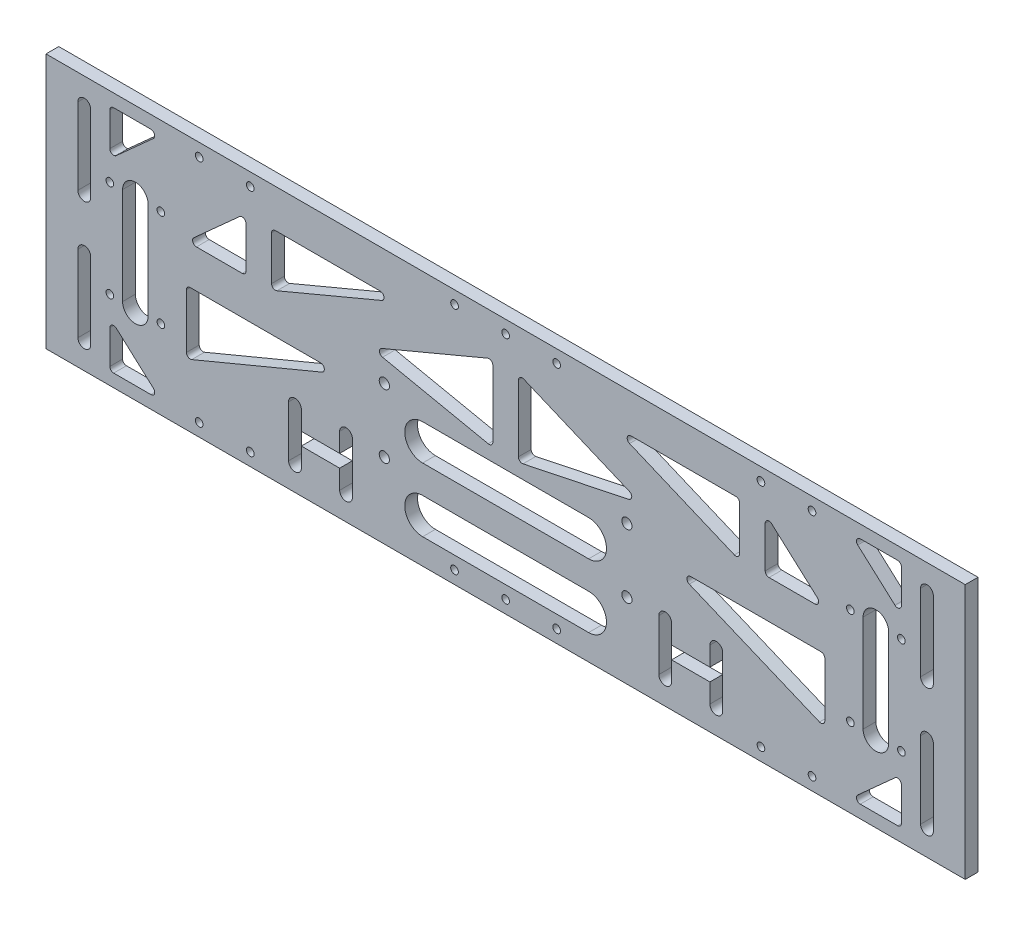
SolidWorks part; units mm, degrees
material "A-玻璃纤维"
ref_plane "前视基准面" through (0, 0, 0) normal (0, 0, 1) x (1, 0, 0)
ref_plane "上视基准面" through (0, 0, 0) normal (0, 1, 0) x (1, 0, 0)
ref_plane "右视基准面" through (0, 0, 0) normal (1, 0, 0) x (0, 0, -1)
sketch "草图1" plane through (0, 0, 0) normal (0, 0, 1) x (1, 0, 0)
  line L1 (0, 0) -> (320, 0)
  line L2 (0, 0) -> (0, 121)
  line L3 (0, 121) -> (320, 121)
  line L4 (320, 0) -> (320, 121)
  dimension "D1" = 320
  dimension "D2" = 121
extrude "凸台-拉伸1" add sketch "草图1" along normal blind 5
sketch "草图2" plane through (0, 0, 5) normal (0, 0, 1) x (1, 0, 0)
  line L0 (160, 121) -> (160, 0) construction
  line L1 (320, 121) -> (0, 121) construction
  line L2 (0, 0) -> (320, 0) construction
  line L3 (0, 121) -> (0, 0) construction
  line L4 (30, 0) -> (35, 0)
  line L5 (30, 0) -> (30, 30)
  line L6 (30, 30) -> (35, 30)
  line L7 (35, 0) -> (35, 30)
  line L8 (285, 0) -> (285, 30)
  line L9 (290, 30) -> (285, 30)
  line L10 (290, 0) -> (290, 30)
  line L11 (290, 0) -> (285, 0)
  dimension "D1" = 30
  dimension "D2" = 30
  dimension "D3" = 5
extrude "切除-拉伸1" cut sketch "草图2" against normal through all
sketch "草图3" plane through (0, 0, 5) normal (0, 0, 1) x (1, 0, 0)
  line L0 (40, 116) -> (60, 116) construction
  line L1 (160, 121) -> (160, 0) construction
  line L2 (320, 121) -> (0, 121) construction
  line L3 (35, 0) -> (285, 0) construction
  line L4 (140, 116) -> (160, 116) construction
  line L5 (0, 121) -> (0, 0) construction
  line L6 (280, 116) -> (260, 116) construction
  circle A0 centre (40, 116) radius 1.5
  circle A1 centre (60, 116) radius 1.5
  circle A2 centre (140, 116) radius 1.5
  circle A3 centre (160, 116) radius 1.5
  circle A4 centre (260, 116) radius 1.5
  circle A5 centre (280, 116) radius 1.5
  circle A6 centre (180, 116) radius 1.5
  dimension "D5" = 3
  dimension "D1" = 40
  dimension "D2" = 5
  dimension "D3" = 20
  dimension "D4" = 20
extrude "切除-拉伸2" cut sketch "草图3" against normal through all
sketch "草图4" plane through (0, 0, 5) normal (0, 0, 1) x (1, 0, 0)
  line L0 (160, 121) -> (160, 0) construction
  line L1 (5, 90) -> (25, 90) construction
  line L2 (5, 90) -> (5, 10) construction
  line L3 (5, 10) -> (25, 10) construction
  line L4 (25, 90) -> (25, 10) construction
  line L5 (320, 121) -> (0, 121) construction
  line L6 (35, 0) -> (285, 0) construction
  line L7 (0, 0) -> (30, 0) construction
  line L8 (0, 121) -> (0, 0) construction
  line L10 (295, 90) -> (295, 10) construction
  line L11 (315, 10) -> (295, 10) construction
  line L12 (315, 90) -> (315, 10) construction
  line L13 (315, 90) -> (295, 90) construction
  circle A0 centre (5, 90) radius 1.5
  circle A1 centre (25, 90) radius 1.5
  circle A2 centre (5, 10) radius 1.5
  circle A3 centre (25, 10) radius 1.5
  circle A4 centre (295, 10) radius 1.5
  circle A5 centre (315, 10) radius 1.5
  circle A6 centre (295, 90) radius 1.5
  circle A7 centre (315, 90) radius 1.5
  dimension "D5" = 3
  dimension "D1" = 10
  dimension "D2" = 80
  dimension "D3" = 5
  dimension "D4" = 20
extrude "切除-拉伸3" cut sketch "草图4" against normal through all
sketch "草图6" plane through (0, 0, 5) normal (0, 0, 1) x (1, 0, 0)
  line L0 (160, 121) -> (160, 0) construction
  line L1 (320, 121) -> (0, 121) construction
  line L2 (35, 0) -> (285, 0) construction
  line L3 (127.5, 63) -> (192.5, 63) construction
  line L4 (112.5, 50.5) -> (207.5, 50.5) construction
  line L5 (112.5, 50.5) -> (112.5, 75.5) construction
  line L6 (112.5, 75.5) -> (207.5, 75.5) construction
  line L7 (207.5, 50.5) -> (207.5, 75.5) construction
  line L8 (112.5, 50.5) -> (207.5, 75.5) construction
  line L9 (112.5, 75.5) -> (207.5, 50.5) construction
  line L10 (127.5, 70) -> (192.5, 70)
  line L11 (127.5, 56) -> (192.5, 56)
  circle A0 centre (112.5, 75.5) radius 2
  circle A1 centre (207.5, 75.5) radius 2
  circle A2 centre (207.5, 50.5) radius 2
  circle A3 centre (112.5, 50.5) radius 2
  arc A4 (127.5, 70) -> (127.5, 56) centre (127.5, 63) ccw
  arc A5 (192.5, 56) -> (192.5, 70) centre (192.5, 63) ccw
  point P6 (160, 63)
  point P17 (160, 63)
  dimension "D1" = 4
  dimension "D5" = 7
  dimension "D2" = 25
  dimension "D3" = 95
  dimension "D4" = 45.5
  dimension "D6" = 15
extrude "切除-拉伸5" cut sketch "草图6" against normal through all
sketch "草图5" plane through (0, 0, 5) normal (0, 0, 1) x (1, 0, 0)
  line L0 (5, 101.368) -> (5, 114.5)
  line L1 (6.5, 116) -> (21.0911, 116)
  line L2 (22.0945, 113.3851) -> (7.5034, 100.2531)
  line L6 (5, 90) -> (25, 90) construction
  line L7 (0, 121) -> (0, 0) construction
  line L8 (320, 121) -> (0, 121) construction
  line L9 (38.9089, 85) -> (56.8333, 85)
  line L10 (58.3333, 86.5) -> (58.3333, 102.632)
  line L11 (55.8299, 103.7469) -> (37.9055, 87.6149)
  line L12 (160, 121) -> (160, 0) construction
  line L13 (35, 0) -> (285, 0) construction
  line L14 (35, 68.5) -> (35, 47.25)
  line L15 (35, 0) -> (285, 0)
  line L16 (35, 0) -> (35, 30)
  line L17 (35, 30) -> (285, 30)
  line L18 (285, 0) -> (285, 30)
  line L19 (37.0769, 45.8654) -> (88.0769, 67.1154)
  line L20 (87.5, 70) -> (36.5, 70)
  line L24 (68.3333, 87.2569) -> (68.3333, 104.5)
  line L25 (69.8333, 106) -> (110.8883, 106)
  line L26 (111.4691, 103.117) -> (70.4142, 85.874)
  line L27 (111.7889, 84.0154) -> (153.1936, 75.3769)
  line L28 (155, 76.8453) -> (155, 102.8738)
  line L29 (152.9192, 104.2567) -> (111.5144, 86.8668)
  line L30 (315, 90) -> (295, 90) construction
  line L31 (167.0808, 104.2567) -> (208.4856, 86.8668)
  line L32 (165, 76.8453) -> (165, 102.8738)
  line L33 (208.2111, 84.0154) -> (166.8064, 75.3769)
  line L34 (208.5309, 103.117) -> (249.5858, 85.874)
  line L35 (250.1667, 106) -> (209.1117, 106)
  line L36 (251.6667, 87.2569) -> (251.6667, 104.5)
  line L40 (232.5, 70) -> (283.5, 70)
  line L41 (282.9231, 45.8654) -> (231.9231, 67.1154)
  line L42 (285, 68.5) -> (285, 47.25)
  line L43 (264.1701, 103.7469) -> (282.0945, 87.6149)
  line L44 (261.6667, 86.5) -> (261.6667, 102.632)
  line L45 (281.0911, 85) -> (263.1667, 85)
  line L46 (297.9055, 113.3851) -> (312.4966, 100.2531)
  line L47 (313.5, 116) -> (298.9089, 116)
  line L48 (315, 101.368) -> (315, 114.5)
  line L52 (192.5, 70) -> (127.5, 70) construction
  arc A2 (155, 102.8738) -> (152.9192, 104.2567) centre (153.5, 102.8738) ccw
  arc A4 (21.0911, 116) -> (22.0945, 113.3851) centre (21.0911, 114.5) cw
  arc A5 (5, 101.368) -> (7.5034, 100.2531) centre (6.5, 101.368) ccw
  arc A6 (5, 114.5) -> (6.5, 116) centre (6.5, 114.5) cw
  arc A7 (56.8333, 85) -> (58.3333, 86.5) centre (56.8333, 86.5) ccw
  arc A8 (38.9089, 85) -> (37.9055, 87.6149) centre (38.9089, 86.5) cw
  arc A9 (58.3333, 102.632) -> (55.8299, 103.7469) centre (56.8333, 102.632) ccw
  arc A10 (88.0769, 67.1154) -> (87.5, 70) centre (87.5, 68.5) ccw
  arc A11 (35, 47.25) -> (37.0769, 45.8654) centre (36.5, 47.25) ccw
  arc A12 (35, 68.5) -> (36.5, 70) centre (36.5, 68.5) cw
  arc A17 (153.1936, 75.3769) -> (155, 76.8453) centre (153.5, 76.8453) ccw
  arc A18 (111.7889, 84.0154) -> (111.5144, 86.8668) centre (112.0953, 85.4838) cw
  arc A19 (68.3333, 87.2569) -> (70.4142, 85.874) centre (69.8333, 87.2569) ccw
  arc A20 (68.3333, 104.5) -> (69.8333, 106) centre (69.8333, 104.5) cw
  arc A21 (110.8883, 106) -> (111.4691, 103.117) centre (110.8883, 104.5) cw
  arc A22 (209.1117, 106) -> (208.5309, 103.117) centre (209.1117, 104.5) ccw
  arc A23 (251.6667, 104.5) -> (250.1667, 106) centre (250.1667, 104.5) ccw
  arc A24 (251.6667, 87.2569) -> (249.5858, 85.874) centre (250.1667, 87.2569) cw
  arc A25 (208.2111, 84.0154) -> (208.4856, 86.8668) centre (207.9047, 85.4838) ccw
  arc A26 (166.8064, 75.3769) -> (165, 76.8453) centre (166.5, 76.8453) cw
  arc A30 (285, 68.5) -> (283.5, 70) centre (283.5, 68.5) ccw
  arc A31 (285, 47.25) -> (282.9231, 45.8654) centre (283.5, 47.25) cw
  arc A32 (231.9231, 67.1154) -> (232.5, 70) centre (232.5, 68.5) cw
  arc A33 (261.6667, 102.632) -> (264.1701, 103.7469) centre (263.1667, 102.632) cw
  arc A34 (281.0911, 85) -> (282.0945, 87.6149) centre (281.0911, 86.5) ccw
  arc A35 (263.1667, 85) -> (261.6667, 86.5) centre (263.1667, 86.5) cw
  arc A36 (315, 114.5) -> (313.5, 116) centre (313.5, 114.5) ccw
  arc A37 (315, 101.368) -> (312.4966, 100.2531) centre (313.5, 101.368) cw
  arc A38 (298.9089, 116) -> (297.9055, 113.3851) centre (298.9089, 114.5) ccw
  arc A39 (165, 102.8738) -> (167.0808, 104.2567) centre (166.5, 102.8738) cw
  point P23 (25, 116)
  point P26 (5, 98)
  point P29 (5, 116)
  point P40 (35, 85)
  point P43 (58.3333, 106)
  point P56 (95, 70)
  point P59 (35, 45)
  point P62 (35, 70)
  point P84 (155, 105.1307)
  point P87 (155, 75)
  point P90 (107.0698, 85)
  point P93 (68.3333, 85)
  point P96 (68.3333, 106)
  point P99 (118.3333, 106)
  point P156 (201.6667, 106)
  point P157 (251.6667, 106)
  point P158 (251.6667, 85)
  point P159 (212.9302, 85)
  point P160 (165, 75)
  point P161 (165, 105.1307)
  point P162 (285, 70)
  point P163 (285, 45)
  point P164 (225, 70)
  point P165 (261.6667, 106)
  point P166 (285, 85)
  point P167 (315, 116)
  point P168 (315, 98)
  point P169 (295, 116)
  point P186 (20, 15)
  point P189 (8, 15)
  point P192 (20, 25)
  point P202 (300, 25)
  point P203 (312, 15)
  point P204 (300, 15)
  dimension "D8" = 1.5
  dimension "D12" = 1.5
  dimension "D16" = 1.5
  dimension "D27" = 1.5
  dimension "D4" = 5
  dimension "D5" = 5
  dimension "D6" = 20
  dimension "D7" = 18
  dimension "D9" = 5
  dimension "D10" = 10
  dimension "D11" = 10
  dimension "D13" = 15
  dimension "D14" = 15
  dimension "D15" = 60
  dimension "D21" = 15
  dimension "D22" = 10
  dimension "D23" = 50
  dimension "D24" = 15
  dimension "D25" = 10
  dimension "D26" = 5
  dimension "D29" = 8
  dimension "D31" = 10
extrude "切除-拉伸4" cut sketch "草图5" against normal through all
sketch "草图7" plane through (0, 0, 0) normal (0, 0, -1) x (-1, 0, 0)
  line L0 (-290, 0) -> (-290, 30)
  line L1 (-290, 30) -> (-30, 30)
  line L2 (-30, 30) -> (-30, 0)
  line L3 (-30, 0) -> (-290, 0)
extrude "凸台-拉伸2" add sketch "草图7" against normal blind 5
sketch "草图8" plane through (0, 0, 0) normal (0, 0, -1) x (-1, 0, 0)
  line L0 (-320, 0) -> (-320, 21)
  line L1 (-320, 0) -> (-320, 121) construction
  line L2 (-320, 21) -> (0, 21)
  line L3 (0, 121) -> (0, 0) construction
  line L4 (0, 21) -> (0, 0)
  line L5 (0, 0) -> (-320, 0)
extrude "切除-拉伸6" cut sketch "草图8" against normal blind 5
sketch "草图9" plane through (0, 0, 0) normal (0, 0, -1) x (-1, 0, 0)
  line L0 (-160, 21) -> (-335, 21)
  line L1 (0, 21) -> (-320, 21) construction
  line L2 (-335, 21) -> (-335, 121)
  line L3 (-335, 121) -> (15, 121)
  line L4 (15, 121) -> (15, 21)
  line L5 (15, 21) -> (-160, 21)
  line L6 (0, 21) -> (0, 121)
  line L7 (-320, 21) -> (-320, 121)
extrude "凸台-拉伸3" add sketch "草图9" against normal blind 5 contours L0 L7 L3 L2 | L6 L5 L4 L3
sketch "草图10" plane through (0, 0, 0) normal (0, 0, -1) x (-1, 0, 0)
  line L0 (-335, 71) -> (-325, 71)
  line L1 (-335, 21) -> (-335, 121) construction
  line L2 (-325, 71) -> (-325, 121)
  line L3 (-335, 121) -> (15, 121) construction
  line L4 (-325, 71) -> (-325, 21)
  line L5 (15, 21) -> (-335, 21) construction
  line L6 (15, 71) -> (5, 71)
  line L7 (15, 121) -> (15, 21) construction
  line L8 (5, 71) -> (5, 121)
  line L9 (5, 71) -> (5, 21)
  line L10 (-325, 71) -> (-325, 81)
  line L11 (-325, 81) -> (-325, 111)
  line L12 (-325, 71) -> (-325, 61)
  line L13 (-325, 61) -> (-325, 31)
  line L14 (-325, 81) -> (-325, 111) construction
  line L15 (-327.5, 81) -> (-327.5, 111)
  line L16 (-322.5, 81) -> (-322.5, 111)
  line L17 (-325, 61) -> (-325, 31) construction
  line L18 (-322.5, 61) -> (-322.5, 31)
  line L19 (-327.5, 61) -> (-327.5, 31)
  line L20 (-160, 21) -> (-160, 121)
  line L21 (5, 61) -> (5, 31) construction
  line L22 (2.5, 61) -> (2.5, 31)
  line L23 (7.5, 61) -> (7.5, 31)
  line L24 (5, 81) -> (5, 111) construction
  line L25 (7.5, 81) -> (7.5, 111)
  line L26 (2.5, 81) -> (2.5, 111)
  arc A0 (-327.5, 81) -> (-322.5, 81) centre (-325, 81) ccw
  arc A1 (-322.5, 111) -> (-327.5, 111) centre (-325, 111) ccw
  arc A2 (-322.5, 61) -> (-327.5, 61) centre (-325, 61) ccw
  arc A3 (-327.5, 31) -> (-322.5, 31) centre (-325, 31) ccw
  arc A4 (2.5, 61) -> (7.5, 61) centre (5, 61) cw
  arc A5 (7.5, 31) -> (2.5, 31) centre (5, 31) cw
  arc A6 (7.5, 81) -> (2.5, 81) centre (5, 81) cw
  arc A7 (2.5, 111) -> (7.5, 111) centre (5, 111) cw
  point P20 (-325, 96)
  point P25 (-325, 46)
  point P34 (5, 46)
  point P41 (5, 96)
  dimension "D1" = 10
  dimension "D2" = 10
  dimension "D3" = 30
  dimension "D4" = 10
  dimension "D5" = 30
extrude "切除-拉伸7" cut sketch "草图10" against normal blind 5 contours L16 A1 L2 L10 A0 | L2 A1 L15 A0 L10 | L4 A3 L18 A2 L12 | L19 A3 L4 L12 A2 | A7 L8 A6 L25 | A7 L26 A6 L8 | A5 L23 A4 L9 | A5 L9 A4 L22
sketch "草图13" plane through (0, 0, 0) normal (0, 0, -1) x (-1, 0, 0)
  line L12 (-192.5, 63) -> (-192.5, 38)
  line L13 (-127.5, 63) -> (-127.5, 38)
  line L14 (-192.5, 38) -> (-127.5, 38) construction
  line L15 (-192.5, 45) -> (-127.5, 45)
  line L16 (-192.5, 31) -> (-127.5, 31)
  line L18 (-305, 63.5) -> (-305, 83.5)
  line L19 (-305, 63.5) -> (-305, 48.5)
  line L23 (-160, 21) -> (-160, 121)
  line L24 (15, 21) -> (-335, 21) construction
  line L25 (-335, 121) -> (15, 121) construction
  arc A1 (-192.5, 45) -> (-192.5, 31) centre (-192.5, 38) ccw
  arc A2 (-127.5, 31) -> (-127.5, 45) centre (-127.5, 38) ccw
  point P16 (-160, 38)
  dimension "D1" = 25
  dimension "D3" = 15
  dimension "D2" = 25
  dimension "D4" = 20
extrude "切除-拉伸8" cut sketch "草图13" against normal blind 5
sketch "草图15" plane through (0, 0, 0) normal (0, 0, -1) x (-1, 0, 0)
  line L0 (-313.5, 116) -> (-298.9089, 116)
  line L1 (-297.9055, 113.3851) -> (-312.4966, 100.2531)
  line L2 (-315, 114.5) -> (-315, 101.368)
  line L3 (-21.0911, 116) -> (-6.5, 116)
  line L4 (-5, 114.5) -> (-5, 101.368)
  line L5 (-7.5034, 100.2531) -> (-22.0945, 113.3851)
  line L6 (-335, 71) -> (15, 71)
  line L7 (-335, 21) -> (-335, 121) construction
  line L8 (15, 121) -> (15, 21) construction
  line L9 (-21.0911, 26) -> (-6.5, 26)
  line L10 (-5, 27.5) -> (-5, 40.632)
  line L11 (-7.5034, 41.7469) -> (-22.0945, 28.6149)
  line L12 (-315, 27.5) -> (-315, 40.632)
  line L13 (-313.5, 26) -> (-298.9089, 26)
  line L14 (-297.9055, 28.6149) -> (-312.4966, 41.7469)
  circle A0 centre (-280, 116) radius 1.5
  circle A1 centre (-260, 116) radius 1.5
  circle A2 centre (-180, 116) radius 1.5
  circle A3 centre (-160, 116) radius 1.5
  circle A4 centre (-140, 116) radius 1.5
  circle A5 centre (-60, 116) radius 1.5
  circle A6 centre (-40, 116) radius 1.5
  circle A7 centre (-25, 90) radius 1.5
  circle A8 centre (-5, 90) radius 1.5
  circle A9 centre (-315, 90) radius 1.5
  circle A10 centre (-295, 90) radius 1.5
  arc A11 (-315, 101.368) -> (-312.4966, 100.2531) centre (-313.5, 101.368) ccw
  arc A12 (-313.5, 116) -> (-315, 114.5) centre (-313.5, 114.5) ccw
  arc A13 (-297.9055, 113.3851) -> (-298.9089, 116) centre (-298.9089, 114.5) ccw
  arc A14 (-21.0911, 116) -> (-22.0945, 113.3851) centre (-21.0911, 114.5) ccw
  arc A15 (-5, 114.5) -> (-6.5, 116) centre (-6.5, 114.5) ccw
  arc A16 (-7.5034, 100.2531) -> (-5, 101.368) centre (-6.5, 101.368) ccw
  circle A17 centre (-25, 52) radius 1.5
  circle A18 centre (-5, 52) radius 1.5
  arc A19 (-5, 27.5) -> (-6.5, 26) centre (-6.5, 27.5) cw
  arc A20 (-7.5034, 41.7469) -> (-5, 40.632) centre (-6.5, 40.632) cw
  arc A21 (-21.0911, 26) -> (-22.0945, 28.6149) centre (-21.0911, 27.5) cw
  circle A22 centre (-40, 26) radius 1.5
  circle A23 centre (-60, 26) radius 1.5
  circle A24 centre (-140, 26) radius 1.5
  circle A25 centre (-160, 26) radius 1.5
  circle A26 centre (-180, 26) radius 1.5
  circle A27 centre (-260, 26) radius 1.5
  circle A28 centre (-280, 26) radius 1.5
  arc A29 (-313.5, 26) -> (-315, 27.5) centre (-313.5, 27.5) cw
  arc A30 (-297.9055, 28.6149) -> (-298.9089, 26) centre (-298.9089, 27.5) cw
  arc A31 (-315, 40.632) -> (-312.4966, 41.7469) centre (-313.5, 40.632) cw
  circle A32 centre (-295, 52) radius 1.5
  circle A33 centre (-315, 52) radius 1.5
extrude "切除-拉伸9" cut sketch "草图15" against normal through all contours A33 | A31 L12 A29 L13 A30 L14 | A32 | A28 | A27 | A26 | A25 | A24 | A23 | A22 | A21 L9 A19 L10 A20 L11 | A18 | A17
sketch "草图16" plane through (0, 0, 0) normal (0, 0, -1) x (-1, 0, 0)
  line L0 (-335, 71) -> (15, 71)
  line L1 (-335, 21) -> (-335, 121) construction
  line L2 (15, 121) -> (15, 21) construction
  line L3 (-315, 90) -> (-295, 90)
  line L4 (-315, 52) -> (-295, 52)
  line L5 (-305, 52) -> (-305, 90)
  line L6 (-305, 52) -> (-305, 90) construction
  line L7 (-310, 52) -> (-310, 90)
  line L8 (-300, 52) -> (-300, 90)
  line L9 (-160, 21) -> (-160, 121)
  line L10 (15, 21) -> (-335, 21) construction
  line L11 (-335, 121) -> (15, 121) construction
  line L12 (-15, 52) -> (-15, 90) construction
  line L13 (-10, 52) -> (-10, 90)
  line L14 (-20, 52) -> (-20, 90)
  arc A0 (-310, 52) -> (-300, 52) centre (-305, 52) ccw
  arc A1 (-300, 90) -> (-310, 90) centre (-305, 90) ccw
  arc A2 (-10, 52) -> (-20, 52) centre (-15, 52) cw
  arc A3 (-20, 90) -> (-10, 90) centre (-15, 90) cw
  point P16 (-305, 71)
  point P29 (-15, 71)
extrude "切除-拉伸10" cut sketch "草图16" against normal through all contours L4 L8 L0 L5 | L4 A0 | L7 L4 L5 L0 | L0 L8 L3 L5 | L7 L0 L5 L3 | L3 A1 | A2 L13 L0 L14 | A3 L14 L0 L13
sketch "草图17" plane through (0, 0, 0) normal (0, 0, -1) x (-1, 0, 0)
  line L0 (-207.5, 50.5) -> (-257.5, 50.5)
  line L1 (-257.5, 50.5) -> (-257.5, 30.5)
  line L2 (-257.5, 30.5) -> (-207.5, 30.5)
  line L3 (-207.5, 30.5) -> (-207.5, 50.5)
  line L4 (-207.5, 40.5) -> (-257.5, 40.5)
  line L5 (-257.5, 50.5) -> (-247.5, 50.5)
  line L6 (-247.5, 50.5) -> (-247.5, 30.5)
  line L7 (-207.5, 50.5) -> (-217.5, 50.5)
  line L8 (-217.5, 50.5) -> (-217.5, 30.5)
  line L9 (-247.5, 50.5) -> (-242.5, 50.5)
  line L10 (-242.5, 50.5) -> (-242.5, 30.5)
  line L11 (-217.5, 50.5) -> (-222.5, 50.5)
  line L12 (-222.5, 50.5) -> (-222.5, 30.5)
  line L13 (-242.5, 50.5) -> (-242.5, 30.5) construction
  line L14 (-240, 50.5) -> (-240, 30.5)
  line L15 (-245, 50.5) -> (-245, 30.5)
  line L16 (-222.5, 50.5) -> (-222.5, 30.5) construction
  line L17 (-220, 50.5) -> (-220, 30.5)
  line L18 (-225, 50.5) -> (-225, 30.5)
  line L19 (-242.5, 40.5) -> (-222.5, 40.5) construction
  line L20 (-242.5, 43) -> (-222.5, 43)
  line L21 (-242.5, 38) -> (-222.5, 38)
  line L22 (-160, 21) -> (-160, 121)
  line L23 (15, 21) -> (-335, 21) construction
  line L24 (-335, 121) -> (15, 121) construction
  line L25 (-97.5, 50.5) -> (-97.5, 30.5) construction
  line L26 (-100, 50.5) -> (-100, 30.5)
  line L27 (-95, 50.5) -> (-95, 30.5)
  line L28 (-77.5, 40.5) -> (-97.5, 40.5) construction
  line L29 (-77.5, 43) -> (-97.5, 43)
  line L30 (-77.5, 38) -> (-97.5, 38)
  line L31 (-77.5, 50.5) -> (-77.5, 30.5) construction
  line L32 (-80, 50.5) -> (-80, 30.5)
  line L33 (-75, 50.5) -> (-75, 30.5)
  arc A0 (-240, 50.5) -> (-245, 50.5) centre (-242.5, 50.5) ccw
  arc A1 (-245, 30.5) -> (-240, 30.5) centre (-242.5, 30.5) ccw
  arc A2 (-220, 50.5) -> (-225, 50.5) centre (-222.5, 50.5) ccw
  arc A3 (-225, 30.5) -> (-220, 30.5) centre (-222.5, 30.5) ccw
  arc A4 (-242.5, 43) -> (-242.5, 38) centre (-242.5, 40.5) ccw
  arc A5 (-222.5, 38) -> (-222.5, 43) centre (-222.5, 40.5) ccw
  arc A6 (-100, 50.5) -> (-95, 50.5) centre (-97.5, 50.5) cw
  arc A7 (-95, 30.5) -> (-100, 30.5) centre (-97.5, 30.5) cw
  arc A8 (-77.5, 43) -> (-77.5, 38) centre (-77.5, 40.5) cw
  arc A9 (-97.5, 38) -> (-97.5, 43) centre (-97.5, 40.5) cw
  arc A10 (-80, 50.5) -> (-75, 50.5) centre (-77.5, 50.5) cw
  arc A11 (-75, 30.5) -> (-80, 30.5) centre (-77.5, 30.5) cw
  point P11 (-242.5, 40.5)
  point P20 (-222.5, 40.5)
  point P25 (-232.5, 40.5)
  point P40 (-97.5, 40.5)
  point P47 (-87.5, 40.5)
  point P54 (-77.5, 40.5)
  dimension "D1" = 20
extrude "切除-拉伸11" cut sketch "草图17" against normal through all contours A11 L33 A8 L30 L32 | A8 L29 L32 L30 | A10 L32 L29 A8 L33 | L32 L29 L27 L30 | A9 L30 L27 L29 | L26 A9 L29 L27 A6 | L30 A9 L26 A7 L27 | L10 L20 L14 L0 | A4 L10 L0 L15 | L0 A0 | L20 L14 L4 L18 | L20 L10 L4 L14 | L10 A4 L4 | L4 A4 L10 | L10 L21 L14 L4 | L14 L21 L18 L4 | L21 L10 L2 L14 | A4 L15 L2 L10 | L2 A1 | L2 A3 | A5 L12 L2 L17 | L21 L18 L2 L12 | L18 L21 L12 L4 | L12 A5 L4 | L4 A5 L12 | L20 L18 L4 L12 | L18 L20 L12 L0 | A5 L17 L11 L12 | L11 A2 L0
sketch "草图18" plane through (0, 0, 0) normal (0, 0, -1) x (-1, 0, 0)
  line L0 (-335, 21) -> (-340, 21)
  line L1 (-340, 21) -> (-340, 121)
  line L2 (-340, 121) -> (-335, 121)
  line L3 (-335, 121) -> (-335, 21)
  line L4 (15, 21) -> (20, 21)
  line L5 (20, 21) -> (20, 121)
  line L6 (20, 121) -> (15, 121)
  line L7 (15, 121) -> (15, 21)
extrude "凸台-拉伸4" add sketch "草图18" against normal blind 5
